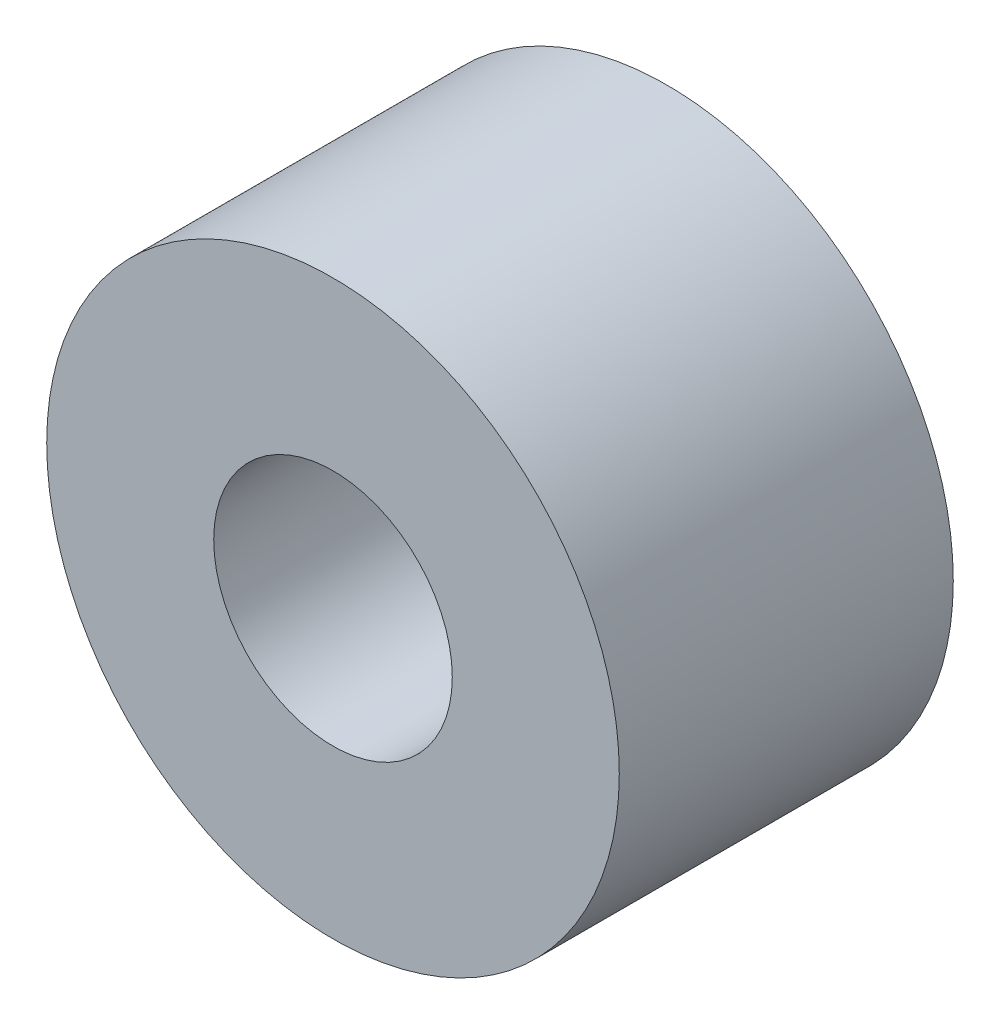
SolidWorks part; units mm, degrees
ref_plane "Front Plane" through (0, 0, 0) normal (0, 0, 1) x (1, 0, 0)
ref_plane "Top Plane" through (0, 0, 0) normal (0, 1, 0) x (1, 0, 0)
ref_plane "Right Plane" through (0, 0, 0) normal (1, 0, 0) x (0, 0, -1)
sketch "Sketch1" plane through (0, 0, 0) normal (0, 0, 1) x (1, 0, 0)
  circle A0 centre (0, 0) radius 2.5
  circle A1 centre (0, 0) radius 6
  dimension "D1" = 5
  dimension "D2" = 12
extrude "Boss-Extrude1" add sketch "Sketch1" along normal blind 7
